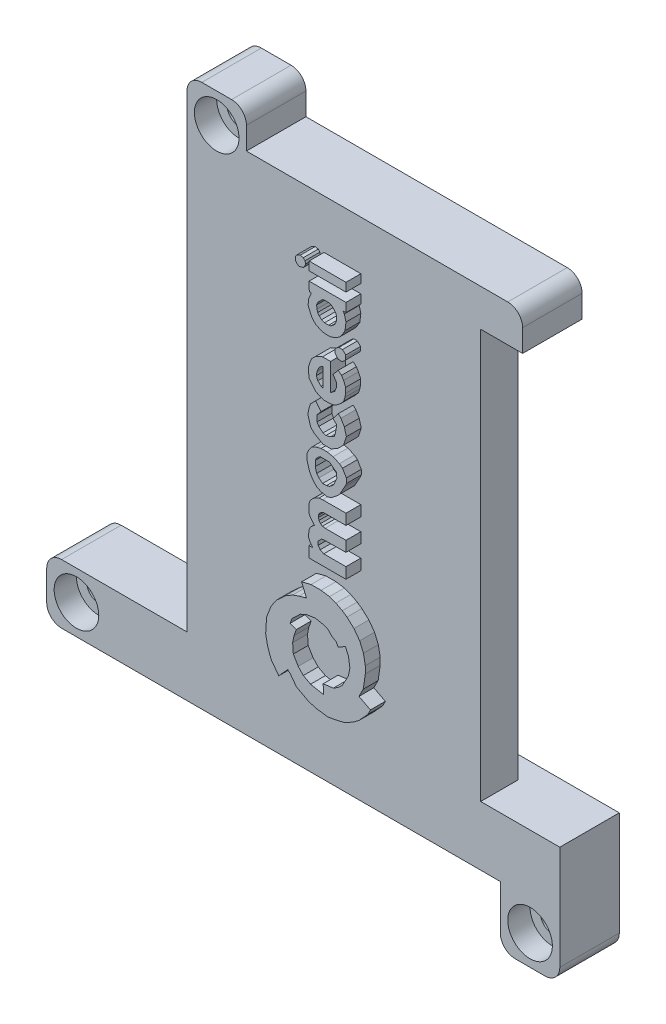
SolidWorks part; units mm, degrees
ref_plane "前视基准面" through (0, 0, 0) normal (0, 0, 1) x (1, 0, 0)
ref_plane "上视基准面" through (0, 0, 0) normal (0, 1, 0) x (1, 0, 0)
ref_plane "右视基准面" through (0, 0, 0) normal (1, 0, 0) x (0, 0, -1)
other "Configuration Table"
sketch "草图1" plane through (0, 0, 0) normal (0, 0, 1) x (1, 0, 0)
  line L0 (-17, 36.5) -> (-17, 23.5)
  line L1 (-17, 23.5) -> (-17, -28.5)
  line L2 (-17, -28.5) -> (-36, -28.5)
  line L3 (-36, -28.5) -> (-36, -36.5)
  line L4 (-36, -36.5) -> (36, -36.5)
  line L5 (36, -36.5) -> (36, -28.5)
  line L6 (36, -28.5) -> (23.5115, -28.5)
  line L8 (21, 31.5) -> (-9, 31.5)
  line L9 (-9, 31.5) -> (-9, 36.5)
  line L10 (-9, 36.5) -> (-17, 36.5)
  line L11 (-36, -32.5) -> (59.8549, -32.5) construction
  line L13 (23.5115, -28.5) -> (21, -28.5)
  line L16 (21, -28.5) -> (21, 31.5)
  dimension "D1" = 8
  dimension "D2" = 8
  dimension "D3" = 8
  dimension "D4" = 72
  dimension "D5" = 52
  dimension "D6" = 13
  dimension "D7" = 5
  dimension "D10" = 30
extrude "凸台-拉伸1" add sketch "草图1" along normal blind 8
sketch "草图2" plane through (0, 0, 8) normal (0, 0, 1) x (1, 0, 0)
  line L0 (-13, 36.5) -> (-13, 18.9568) construction
  line L1 (-9, 36.5) -> (-17, 36.5) construction
  line L2 (-36, -32.5) -> (46.5227, -32.5) construction
  line L3 (-36, -28.5) -> (-36, -36.5) construction
  line L4 (36, -36.5) -> (36, -28.5) construction
  circle A0 centre (-13, 32.5) radius 1.6
  circle A1 centre (-32, -32.5) radius 1.6
  circle A2 centre (32, -32.5) radius 1.6
  dimension "D1" = 3.2
  dimension "D4" = 3.2
  dimension "D5" = 3.2
  dimension "D2" = 4
  dimension "D3" = 4
  dimension "D6" = 4
extrude "切除-拉伸1" cut sketch "草图2" against normal through all
fillet "圆角1" radius 2 6 edges at (-36, -36.5, 4) (-36, -28.5, 4) (36, -36.5, 4) (36, -28.5, 4) (-9, 36.5, 4) (-17, 36.5, 4)
sketch "草图3" plane through (0, 0, 8) normal (0, 0, 1) x (1, 0, 0)
  circle A0 centre (-13, 32.5) radius 3
  circle A1 centre (-32, -32.5) radius 3
  circle A2 centre (32, -32.5) radius 3
  dimension "D1" = 6
  dimension "D2" = 6
  dimension "D3" = 6
extrude "切除-拉伸2" cut sketch "草图3" against normal blind 3
sketch "草图4" plane through (0, 0, 8) normal (0, 0, 1) x (1, 0, 0)
  line L0 (34, -28.5) -> (21, -28.5) construction
  line L1 (21, 31.5) -> (22.5, 31.5)
  line L2 (21, 31.5) -> (21, -28.5)
  line L3 (21, -28.5) -> (22.5, -28.5)
  line L4 (22.5, 31.5) -> (22.5, -28.5)
  dimension "D1" = 1.5
extrude "凸台-拉伸2" add sketch "草图4" against normal up to surface (8 mm away) up to face at (-11.4, 32.5, 0)
sketch "草图5" plane through (0, 0, 8) normal (0, 0, 1) x (1, 0, 0)
  line L0 (34, -28.5) -> (22.5, -28.5) construction
  line L1 (28, -28.5) -> (36, -28.5)
  line L2 (28, -28.5) -> (28, -36.5)
  line L3 (28, -36.5) -> (36, -36.5)
  line L4 (36, -28.5) -> (36, -36.5)
  line L5 (-34, -36.5) -> (34, -36.5) construction
  line L6 (36, -34.5) -> (36, -30.5) construction
  dimension "D1" = 0
  dimension "D2" = 0
  dimension "D3" = 8
extrude "切除-拉伸3" cut sketch "草图5" against normal through all
sketch "草图6" plane through (0, 0, 8) normal (0, 0, 1) x (1, 0, 0)
  line L0 (20, -36.5) -> (28, -44.5) construction
  line L1 (28, -36.5) -> (20, -36.5)
  line L2 (28, -36.5) -> (28, -44.5)
  line L3 (28, -44.5) -> (20, -44.5)
  line L4 (20, -36.5) -> (20, -44.5)
  circle A0 centre (24, -40.5) radius 1.6
  dimension "D3" = 3.2
  dimension "D1" = 8
  dimension "D2" = 8
sketch "草图8" plane through (0, 0, 8) normal (0, 0, 1) x (1, 0, 0)
  line L0 (28, -36.5) -> (20, -36.5) construction
  line L1 (28, -28.5) -> (33.14, -28.5)
  line L2 (28, -28.5) -> (28, -36.5)
  line L3 (28, -36.5) -> (33.14, -36.5)
  line L4 (33.14, -28.5) -> (33.14, -36.5)
  dimension "D1" = 5.14
  dimension "D2" = 0
extrude "凸台-拉伸4" add sketch "草图8" against normal up to surface (8 mm away) up to face at (-8.4163, -3.298, 0)
sketch "草图9" plane through (0, 0, 8) normal (0, 0, 1) x (1, 0, 0)
  line L0 (25.14, -36.5) -> (33.14, -44.5) construction
  line L1 (33.14, -36.5) -> (25.14, -36.5)
  line L2 (33.14, -36.5) -> (33.14, -44.5)
  line L3 (33.14, -44.5) -> (25.14, -44.5)
  line L4 (25.14, -36.5) -> (25.14, -44.5)
  circle A0 centre (29.14, -40.5) radius 1.6
  dimension "D3" = 3.2
  dimension "D1" = 8
  dimension "D2" = 8
extrude "凸台-拉伸5" add sketch "草图9" against normal up to surface (8 mm away) up to face at (-7.682, -3.298, 0)
sketch "草图10" plane through (0, 0, 8) normal (0, 0, 1) x (1, 0, 0)
  circle A0 centre (29.14, -40.5) radius 3
  dimension "D1" = 6
extrude "切除-拉伸5" cut sketch "草图10" against normal blind 3
fillet "圆角3" radius 2 2 edges at (25.14, -44.5, 4) (33.14, -44.5, 4)
sketch "草图11" plane through (22.5, 0, 0) normal (1, 0, 0) x (0, 0, -1)
  line L0 (-8, 36.5) -> (0, 36.5) construction
  line L1 (0, -28.5) -> (-3, -28.5)
  line L2 (0, -28.5) -> (0, 23.5)
  line L3 (0, 23.5) -> (-3, 23.5)
  line L4 (-3, -28.5) -> (-3, 23.5)
  dimension "D1" = 13
  dimension "D2" = 3
extrude "切除-拉伸6" cut sketch "草图11" against normal through all
sketch "草图13" plane through (0, 0, 8) normal (0, 0, 1) x (1, 0, 0)
  line L1 (22.5, 31.5) -> (28.14, 31.5)
  line L2 (22.5, 31.5) -> (22.5, 26.5)
  line L3 (22.5, 26.5) -> (28.14, 26.5)
  line L4 (28.14, 31.5) -> (28.14, 26.5)
  dimension "D1" = 5.64
  dimension "D2" = 5
extrude "凸台-拉伸6" add sketch "草图13" against normal up to surface (8 mm away) up to face at (-4.125, 31.6036, 0)
fillet "圆角4" radius 2 1 edges at (28.14, 31.5, 4)
sketch "草图14" plane through (0, 0, 8) normal (0, 0, 1) x (1, 0, 0)
  line L0 (1.4021, -9.6793) -> (6.3817, -9.6793)
  line L1 (6.3817, -9.6793) -> (6.3817, -8.2117)
  line L2 (6.3817, -8.2117) -> (3.3939, -8.2117)
  line L3 (3.3939, -8.2117) -> (2.9222, -7.967)
  line L4 (2.9222, -7.967) -> (2.6426, -7.6001)
  line L5 (2.6426, -7.6001) -> (2.6426, -7.0934)
  line L6 (2.6426, -7.0934) -> (2.8872, -6.8488)
  line L7 (2.8872, -6.8488) -> (3.0946, -6.6415)
  line L8 (3.0946, -6.6415) -> (3.3414, -6.5738)
  line L9 (3.3414, -6.5738) -> (6.3817, -6.5465)
  line L10 (6.3817, -6.5465) -> (6.3817, -5.1381)
  line L11 (6.3817, -5.1381) -> (3.583, -5.1381)
  line L12 (3.583, -5.1381) -> (3.218, -5.0834)
  line L13 (3.218, -5.0834) -> (2.954, -4.9102)
  line L14 (2.954, -4.9102) -> (2.7649, -4.6321)
  line L15 (2.7649, -4.6321) -> (2.6817, -4.3285)
  line L16 (2.6817, -4.3285) -> (2.6817, -4.0852)
  line L17 (2.6817, -4.0852) -> (2.8127, -3.7889)
  line L18 (2.8127, -3.7889) -> (3.0338, -3.5679)
  line L19 (3.0338, -3.5679) -> (3.313, -3.4153)
  line L20 (3.313, -3.4153) -> (3.7559, -3.4153)
  line L21 (3.7559, -3.4153) -> (6.3817, -3.4153)
  line L22 (6.3817, -3.4153) -> (6.3817, -1.9824)
  line L23 (6.3817, -1.9824) -> (3.249, -1.9824)
  line L24 (3.249, -1.9824) -> (2.7472, -2.0375)
  line L25 (2.7472, -2.0375) -> (2.2559, -2.2546)
  line L26 (2.2559, -2.2546) -> (1.9572, -2.4913)
  line L27 (1.9572, -2.4913) -> (1.6941, -2.7544)
  line L28 (1.6941, -2.7544) -> (1.5228, -3.0155)
  line L29 (1.5228, -3.0155) -> (1.4021, -3.3844)
  line L30 (1.4021, -3.3844) -> (1.4021, -4.4317)
  line L31 (1.4021, -4.4317) -> (1.573, -4.8186)
  line L32 (1.573, -4.8186) -> (1.8045, -5.1107)
  line L33 (1.8045, -5.1107) -> (2.0378, -5.405)
  line L34 (2.0378, -5.405) -> (2.1294, -5.5205)
  line L35 (2.1294, -5.5205) -> (1.8045, -5.7781)
  line L36 (1.8045, -5.7781) -> (1.573, -6.0778)
  line L37 (1.573, -6.0778) -> (1.4358, -6.388)
  line L38 (1.4358, -6.388) -> (1.3667, -6.8488)
  line L39 (1.3667, -6.8488) -> (1.3667, -7.3296)
  line L40 (1.3667, -7.3296) -> (1.4781, -7.5818)
  line L41 (1.4781, -7.5818) -> (1.622, -7.8452)
  line L42 (1.622, -7.8452) -> (1.8045, -8.0754)
  line L43 (1.8045, -8.0754) -> (1.967, -8.2379)
  line L44 (1.967, -8.2379) -> (1.4224, -8.2379)
  line L45 (1.4224, -8.2379) -> (1.4021, -9.6793)
  line L46 (2.7472, 2.7611) -> (2.3778, 2.3917)
  line L47 (2.3778, 2.3917) -> (2.2559, 2.1159)
  line L48 (2.2559, 2.1159) -> (2.2559, 1.3832)
  line L49 (2.2559, 1.3832) -> (2.4483, 0.681)
  line L50 (2.4483, 0.681) -> (2.7472, 0.3039)
  line L51 (2.7472, 0.3039) -> (3.249, -0.0838)
  line L52 (3.249, -0.0838) -> (3.7559, -0.0838)
  line L53 (3.7559, -0.0838) -> (4.1708, 0.0299)
  line L54 (4.1708, 0.0299) -> (4.6942, 0.4448)
  line L55 (4.6942, 0.4448) -> (4.9539, 1.0321)
  line L56 (4.9539, 1.0321) -> (5.1595, 1.4969)
  line L57 (5.1595, 1.4969) -> (5.0867, 2.1589)
  line L58 (5.0867, 2.1589) -> (4.6454, 2.5)
  line L59 (4.6454, 2.5) -> (4.1708, 2.8666)
  line L60 (4.1708, 2.8666) -> (3.5345, 2.8666)
  line L61 (3.5345, 2.8666) -> (2.9232, 2.8666)
  line L62 (2.9232, 2.8666) -> (2.7472, 2.7611)
  line L63 (1.1749, 1.8279) -> (1.1749, 2.3917)
  line L64 (1.1749, 2.3917) -> (1.4021, 2.9054)
  line L65 (1.4021, 2.9054) -> (1.8257, 3.4536)
  line L66 (1.8257, 3.4536) -> (2.4483, 3.7287)
  line L67 (2.4483, 3.7287) -> (3.0338, 3.8891)
  line L68 (3.0338, 3.8891) -> (3.8526, 3.8891)
  line L69 (3.8526, 3.8891) -> (4.6454, 3.7287)
  line L70 (4.6454, 3.7287) -> (5.0867, 3.5335)
  line L71 (5.0867, 3.5335) -> (5.5015, 3.35)
  line L72 (5.5015, 3.35) -> (5.9214, 3.0256)
  line L73 (5.9214, 3.0256) -> (6.1907, 2.5764)
  line L74 (6.1907, 2.5764) -> (6.4409, 2.1589)
  line L75 (6.4409, 2.1589) -> (6.4409, 1.4969)
  line L76 (6.4409, 1.4969) -> (6.2607, 1.0894)
  line L77 (6.2607, 1.0894) -> (5.7814, 0.2373)
  line L78 (5.7814, 0.2373) -> (5.5371, -0.1971)
  line L79 (5.5371, -0.1971) -> (5.1595, -0.5747)
  line L80 (5.1595, -0.5747) -> (4.4081, -1.1704)
  line L81 (4.4081, -1.1704) -> (3.8526, -1.3226)
  line L82 (3.8526, -1.3226) -> (3.0602, -1.1622)
  line L83 (3.0602, -1.1622) -> (2.5015, -0.9152)
  line L84 (2.5015, -0.9152) -> (1.9572, -0.3709)
  line L85 (1.9572, -0.3709) -> (1.5228, 0.3538)
  line L86 (1.5228, 0.3538) -> (1.2885, 1.0894)
  line L87 (1.2885, 1.0894) -> (1.1386, 1.6364)
  line L88 (1.1386, 1.6364) -> (1.1749, 1.8279)
  line L89 (3.0338, 8.1758) -> (2.3169, 9.0802)
  line L90 (2.3169, 9.0802) -> (1.6139, 8.3772)
  line L91 (1.6139, 8.3772) -> (1.4021, 7.7302)
  line L92 (1.4021, 7.7302) -> (1.2625, 6.9942)
  line L93 (1.2625, 6.9942) -> (1.4694, 6.2391)
  line L94 (1.4694, 6.2391) -> (1.6586, 5.6451)
  line L95 (1.6586, 5.6451) -> (2.137, 5.1668)
  line L96 (2.137, 5.1668) -> (3.313, 4.5054)
  line L97 (3.313, 4.5054) -> (4.4081, 4.5054)
  line L98 (4.4081, 4.5054) -> (5.3483, 5.0689)
  line L99 (5.3483, 5.0689) -> (6.0561, 5.7767)
  line L100 (6.0561, 5.7767) -> (6.2686, 6.4259)
  line L101 (6.2686, 6.4259) -> (6.4409, 6.9524)
  line L102 (6.4409, 6.9524) -> (6.1623, 7.9689)
  line L103 (6.1623, 7.9689) -> (5.7022, 8.7366)
  line L104 (5.7022, 8.7366) -> (5.3483, 9.0905)
  line L105 (5.3483, 9.0905) -> (4.6416, 8.1758)
  line L106 (4.6416, 8.1758) -> (5.0872, 7.7302)
  line L107 (5.0872, 7.7302) -> (5.0872, 7.3245)
  line L108 (5.0872, 7.3245) -> (4.953, 6.6167)
  line L109 (4.953, 6.6167) -> (4.8114, 6.1841)
  line L110 (4.8114, 6.1841) -> (4.315, 5.8866)
  line L111 (4.315, 5.8866) -> (3.6838, 5.7136)
  line L112 (3.6838, 5.7136) -> (3.313, 5.835)
  line L113 (3.313, 5.835) -> (2.725, 6.2893)
  line L114 (2.725, 6.2893) -> (2.4832, 6.6927)
  line L115 (2.4832, 6.6927) -> (2.4832, 7.5274)
  line L116 (2.4832, 7.5274) -> (3.0338, 8.1758)
  line L117 (4.6416, 13.3099) -> (5.3483, 14.1423)
  line L118 (5.3483, 14.1423) -> (5.7814, 13.7746)
  line L119 (5.7814, 13.7746) -> (6.0561, 13.3164)
  line L120 (6.0561, 13.3164) -> (6.3483, 12.6548)
  line L121 (6.3483, 12.6548) -> (6.3483, 11.9848)
  line L122 (6.3483, 11.9848) -> (6.249, 11.461)
  line L123 (6.249, 11.461) -> (6.0561, 10.8717)
  line L124 (6.0561, 10.8717) -> (5.7022, 10.4549)
  line L125 (5.7022, 10.4549) -> (4.9949, 9.8942)
  line L126 (4.9949, 9.8942) -> (4.315, 9.7079)
  line L127 (4.315, 9.7079) -> (3.313, 9.7079)
  line L128 (3.313, 9.7079) -> (2.3169, 10.1484)
  line L129 (2.3169, 10.1484) -> (1.8506, 10.7366)
  line L130 (1.8506, 10.7366) -> (1.4265, 11.2715)
  line L131 (1.4265, 11.2715) -> (1.3481, 11.9848)
  line L132 (1.3481, 11.9848) -> (1.3481, 12.5683)
  line L133 (1.3481, 12.5683) -> (1.5523, 13.1922)
  line L134 (1.5523, 13.1922) -> (1.7885, 13.7261)
  line L135 (1.7885, 13.7261) -> (2.3169, 14.2545)
  line L136 (2.3169, 14.2545) -> (2.6753, 14.4129)
  line L137 (2.6753, 14.4129) -> (3.2289, 14.6574)
  line L138 (3.2289, 14.6574) -> (3.8605, 14.6574)
  line L139 (3.8605, 14.6574) -> (4.315, 14.6574)
  line L140 (4.315, 14.6574) -> (4.315, 11.004)
  line L141 (4.315, 11.004) -> (4.8644, 11.4396)
  line L142 (4.8644, 11.4396) -> (5.0872, 11.9434)
  line L143 (5.0872, 11.9434) -> (5.0872, 12.6548)
  line L144 (5.0872, 12.6548) -> (4.6416, 13.3099)
  line L145 (3.313, 13.5455) -> (3.313, 11.004)
  line L146 (3.313, 11.004) -> (3.0338, 11.1275)
  line L147 (3.0338, 11.1275) -> (2.6041, 11.5572)
  line L148 (2.6041, 11.5572) -> (2.3922, 12.0371)
  line L149 (2.3922, 12.0371) -> (2.4981, 12.5958)
  line L150 (2.4981, 12.5958) -> (2.7367, 13.1352)
  line L151 (2.7367, 13.1352) -> (3.0338, 13.4323)
  line L152 (3.0338, 13.4323) -> (3.313, 13.5455)
  line L153 (5.6593, 16.8514) -> (5.9188, 16.8514)
  line L154 (5.9188, 16.8514) -> (6.0874, 16.6828)
  line L155 (6.0874, 16.6828) -> (6.3483, 16.4218)
  line L156 (6.3483, 16.4218) -> (6.3483, 16.0911)
  line L157 (6.3483, 16.0911) -> (6.2906, 15.787)
  line L158 (6.2906, 15.787) -> (6.0874, 15.5838)
  line L159 (6.0874, 15.5838) -> (5.836, 15.4128)
  line L160 (5.836, 15.4128) -> (5.3483, 15.4196)
  line L161 (5.3483, 15.4196) -> (5.1231, 15.6448)
  line L162 (5.1231, 15.6448) -> (4.923, 15.939)
  line L163 (4.923, 15.939) -> (4.923, 16.4218)
  line L164 (4.923, 16.4218) -> (5.1673, 16.6662)
  line L165 (5.1673, 16.6662) -> (5.4397, 16.8514)
  line L166 (5.4397, 16.8514) -> (5.6593, 16.8514)
  line L167 (2.6753, 20.7788) -> (3.0542, 21.1577)
  line L168 (3.0542, 21.1577) -> (3.295, 21.3486)
  line L169 (3.295, 21.3486) -> (3.5447, 21.376)
  line L170 (3.5447, 21.376) -> (3.9274, 21.376)
  line L171 (3.9274, 21.376) -> (4.2254, 21.376)
  line L172 (4.2254, 21.376) -> (4.5361, 21.1722)
  line L173 (4.5361, 21.1722) -> (4.7838, 20.9245)
  line L174 (4.7838, 20.9245) -> (4.9949, 20.6581)
  line L175 (4.9949, 20.6581) -> (5.1026, 20.3928)
  line L176 (5.1026, 20.3928) -> (5.1386, 20.0655)
  line L177 (5.1386, 20.0655) -> (5.0862, 19.7163)
  line L178 (5.0862, 19.7163) -> (4.8894, 19.2711)
  line L179 (4.8894, 19.2711) -> (4.6062, 18.988)
  line L180 (4.6062, 18.988) -> (4.3808, 18.8346)
  line L181 (4.3808, 18.8346) -> (4.0481, 18.7434)
  line L182 (4.0481, 18.7434) -> (3.4984, 18.7512)
  line L183 (3.4984, 18.7512) -> (3.1121, 18.922)
  line L184 (3.1121, 18.922) -> (2.7718, 19.2109)
  line L185 (2.7718, 19.2109) -> (2.5795, 19.4937)
  line L186 (2.5795, 19.4937) -> (2.4832, 19.8449)
  line L187 (2.4832, 19.8449) -> (2.4341, 20.2922)
  line L188 (2.4341, 20.2922) -> (2.5625, 20.5827)
  line L189 (2.5625, 20.5827) -> (2.6753, 20.7788)
  line L190 (1.4265, 22.5667) -> (6.3817, 22.5667)
  line L191 (6.3817, 22.5667) -> (6.3817, 21.376)
  line L192 (6.3817, 21.376) -> (6.0006, 21.376)
  line L193 (6.0006, 21.376) -> (6.1623, 21.106)
  line L194 (6.1623, 21.106) -> (6.249, 20.7788)
  line L195 (6.249, 20.7788) -> (6.3817, 20.2779)
  line L196 (6.3817, 20.2779) -> (6.3153, 19.7163)
  line L197 (6.3153, 19.7163) -> (6.2556, 19.2109)
  line L198 (6.2556, 19.2109) -> (6.0006, 18.7434)
  line L199 (6.0006, 18.7434) -> (5.599, 18.1844)
  line L200 (5.599, 18.1844) -> (5.1673, 17.8563)
  line L201 (5.1673, 17.8563) -> (4.7838, 17.6953)
  line L202 (4.7838, 17.6953) -> (4.347, 17.5119)
  line L203 (4.347, 17.5119) -> (3.583, 17.5119)
  line L204 (3.583, 17.5119) -> (3.1121, 17.6036)
  line L205 (3.1121, 17.6036) -> (2.3169, 17.9713)
  line L206 (2.3169, 17.9713) -> (1.7885, 18.5233)
  line L207 (1.7885, 18.5233) -> (1.5934, 18.988)
  line L208 (1.5934, 18.988) -> (1.2991, 19.6888)
  line L209 (1.2991, 19.6888) -> (1.3481, 20.4496)
  line L210 (1.3481, 20.4496) -> (1.5523, 20.9245)
  line L211 (1.5523, 20.9245) -> (1.7347, 21.3486)
  line L212 (1.7347, 21.3486) -> (1.4502, 21.3486)
  line L213 (1.4502, 21.3486) -> (1.4265, 22.5667)
  line L214 (0.2391, 24.9901) -> (0.651, 24.9099)
  line L215 (0.651, 24.9099) -> (0.8778, 24.673)
  line L216 (0.8778, 24.673) -> (0.9676, 24.3339)
  line L217 (0.9676, 24.3339) -> (0.8291, 24.0121)
  line L218 (0.8291, 24.0121) -> (0.651, 23.7641)
  line L219 (0.651, 23.7641) -> (0.4158, 23.7018)
  line L220 (0.4158, 23.7018) -> (0.0686, 23.6098)
  line L221 (0.0686, 23.6098) -> (-0.1462, 23.7641)
  line L222 (-0.1462, 23.7641) -> (-0.4342, 24.065)
  line L223 (-0.4342, 24.065) -> (-0.4342, 24.5035)
  line L224 (-0.4342, 24.5035) -> (-0.2274, 24.7914)
  line L225 (-0.2274, 24.7914) -> (0.0038, 24.8885)
  line L226 (0.0038, 24.8885) -> (0.2391, 24.9901)
  line L227 (1.4265, 24.9099) -> (1.4265, 23.7641)
  line L228 (1.4265, 23.7641) -> (6.3817, 23.7641)
  line L229 (6.3817, 23.7641) -> (6.3817, 24.9099)
  line L230 (6.3817, 24.9099) -> (1.4265, 24.9099)
  line L231 (-1.1314, -18.5634) -> (-0.2902, -18.8682)
  line L232 (-0.2902, -18.8682) -> (-0.6129, -19.7585)
  line L233 (-0.6129, -19.7585) -> (-0.7854, -20.6445)
  line L234 (-0.7854, -20.6445) -> (-0.6991, -21.9261)
  line L235 (-0.6991, -21.9261) -> (-0.0388, -23.0288)
  line L236 (-0.0388, -23.0288) -> (0.651, -23.7495)
  line L237 (0.651, -23.7495) -> (1.622, -24.2792)
  line L238 (1.622, -24.2792) -> (2.4483, -24.4401)
  line L239 (2.4483, -24.4401) -> (3.3939, -24.6242)
  line L240 (3.3939, -24.6242) -> (3.3108, -23.3892)
  line L241 (3.3108, -23.3892) -> (4.6942, -23.1914)
  line L242 (4.6942, -23.1914) -> (5.3483, -22.7998)
  line L243 (5.3483, -22.7998) -> (5.8879, -22.2833)
  line L244 (5.8879, -22.2833) -> (6.282, -21.5607)
  line L245 (6.282, -21.5607) -> (6.7057, -20.784)
  line L246 (6.7057, -20.784) -> (6.9054, -19.7585)
  line L247 (6.9054, -19.7585) -> (6.7265, -18.5066)
  line L248 (6.7265, -18.5066) -> (6.3095, -17.5412)
  line L249 (6.3095, -17.5412) -> (5.3483, -18.1167)
  line L250 (5.3483, -18.1167) -> (5.0212, -17.5705)
  line L251 (5.0212, -17.5705) -> (4.5159, -17.2948)
  line L252 (4.5159, -17.2948) -> (3.9538, -16.7076)
  line L253 (3.9538, -16.7076) -> (3.3108, -16.4746)
  line L254 (3.3108, -16.4746) -> (2.2559, -16.2692)
  line L255 (2.2559, -16.2692) -> (1.1365, -16.4291)
  line L256 (1.1365, -16.4291) -> (0.2422, -16.8154)
  line L257 (0.2422, -16.8154) -> (-0.2902, -17.3251)
  line L258 (-0.2902, -17.3251) -> (-0.891, -17.9002)
  line L259 (-0.891, -17.9002) -> (-1.1314, -18.5634)
  line L260 (1.0735, -14.5198) -> (0.4158, -12.9597)
  line L261 (0.4158, -12.9597) -> (1.6941, -12.6355)
  line L262 (1.6941, -12.6355) -> (3.0338, -12.6355)
  line L263 (3.0338, -12.6355) -> (4.1708, -12.7976)
  line L264 (4.1708, -12.7976) -> (5.0212, -13.1319)
  line L265 (5.0212, -13.1319) -> (5.8879, -13.5776)
  line L266 (5.8879, -13.5776) -> (6.5138, -14.0133)
  line L267 (6.5138, -14.0133) -> (7.4559, -14.8744)
  line L268 (7.4559, -14.8744) -> (8.2259, -15.9179)
  line L269 (8.2259, -15.9179) -> (8.7327, -17.1201)
  line L270 (8.7327, -17.1201) -> (8.9857, -18.4404)
  line L271 (8.9857, -18.4404) -> (8.9857, -19.3955)
  line L272 (8.9857, -19.3955) -> (8.8767, -20.1597)
  line L273 (8.8767, -20.1597) -> (8.7128, -21.3097)
  line L274 (8.7128, -21.3097) -> (8.1294, -22.4439)
  line L275 (8.1294, -22.4439) -> (9.6799, -23.2414)
  line L276 (9.6799, -23.2414) -> (9.312, -23.9567)
  line L277 (9.312, -23.9567) -> (8.7742, -24.5451)
  line L278 (8.7742, -24.5451) -> (8.1294, -25.2506)
  line L279 (8.1294, -25.2506) -> (7.3828, -25.8015)
  line L280 (7.3828, -25.8015) -> (6.282, -26.4338)
  line L281 (6.282, -26.4338) -> (5.3483, -26.6706)
  line L282 (5.3483, -26.6706) -> (3.9538, -26.9378)
  line L283 (3.9538, -26.9378) -> (2.4483, -26.7232)
  line L284 (2.4483, -26.7232) -> (1.4021, -26.4338)
  line L285 (1.4021, -26.4338) -> (-0.2902, -25.5261)
  line L286 (-0.2902, -25.5261) -> (-1.0915, -24.4401)
  line L287 (-1.0915, -24.4401) -> (-1.4465, -24.1157)
  line L288 (-1.4465, -24.1157) -> (-2.6552, -25.4382)
  line L289 (-2.6552, -25.4382) -> (-3.6866, -24.0404)
  line L290 (-3.6866, -24.0404) -> (-4.1686, -22.6839)
  line L291 (-4.1686, -22.6839) -> (-4.4139, -21.4035)
  line L292 (-4.4139, -21.4035) -> (-4.2913, -19.3955)
  line L293 (-4.2913, -19.3955) -> (-3.665, -17.8023)
  line L294 (-3.665, -17.8023) -> (-2.9347, -16.7531)
  line L295 (-2.9347, -16.7531) -> (-2.1655, -16.0522)
  line L296 (-2.1655, -16.0522) -> (-1.6952, -15.6237)
  line L297 (-1.6952, -15.6237) -> (-0.7854, -15.1011)
  line L298 (-0.7854, -15.1011) -> (0.0686, -14.7976)
  line L299 (0.0686, -14.7976) -> (1.0735, -14.5198)
extrude "凸台-拉伸7" add sketch "草图14" along normal blind 2
sketch "草图16" plane through (0, 0, 8) normal (0, 0, 1) x (1, 0, 0)
  line L1 (-17, -28.5) -> (-43.2418, -28.5)
  line L2 (-17, -28.5) -> (-17, -46.1758)
  line L3 (-17, -46.1758) -> (-43.2418, -46.1758)
  line L4 (-43.2418, -28.5) -> (-43.2418, -46.1758)
extrude "切除-拉伸7" cut sketch "草图16" against normal through all
sketch "草图17" plane through (0, 0, 8) normal (0, 0, 1) x (1, 0, 0)
  line L1 (-17, -36.5) -> (-35.86, -36.5)
  line L2 (-17, -36.5) -> (-17, -28.5)
  line L3 (-17, -28.5) -> (-35.86, -28.5)
  line L4 (-35.86, -36.5) -> (-35.86, -28.5)
  circle A0 centre (-31.86, -32.5) radius 1.6
  dimension "D5" = 3.2
  dimension "D1" = 18.86
  dimension "D2" = 8
  dimension "D3" = 4
  dimension "D4" = 4
extrude "凸台-拉伸8" add sketch "草图17" against normal up to surface (8 mm away) up to face at (30.74, -40.5, 0)
sketch "草图18" plane through (0, 0, 8) normal (0, 0, 1) x (1, 0, 0)
  circle A0 centre (-31.86, -32.5) radius 3
  dimension "D1" = 6
extrude "切除-拉伸8" cut sketch "草图18" against normal blind 3
fillet "圆角5" radius 2 2 edges at (-35.86, -36.5, 4) (-35.86, -28.5, 4)
